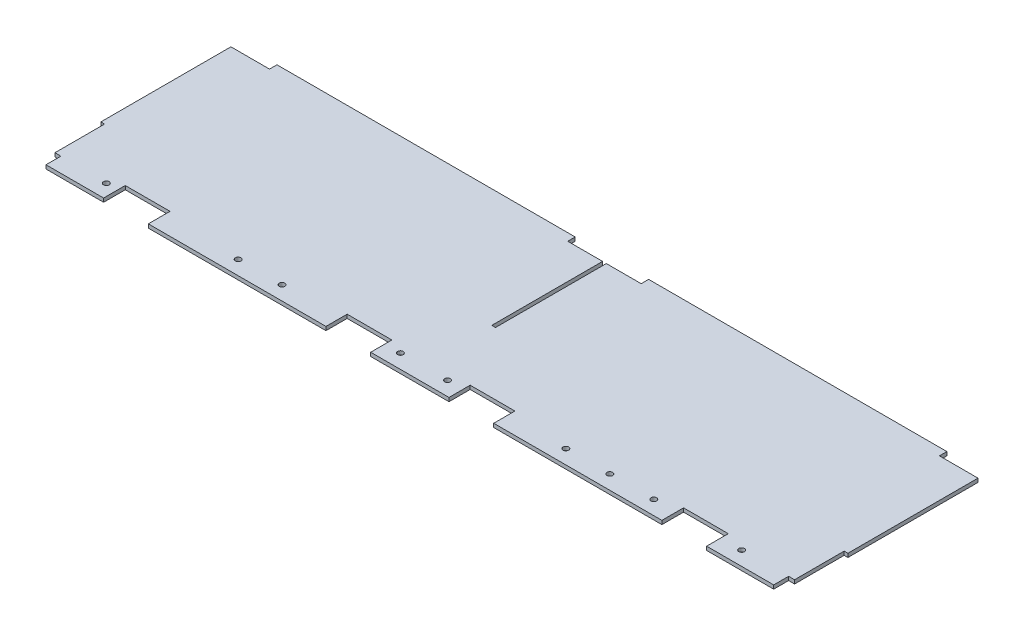
SolidWorks part; units mm, degrees
material "6061-T6 (SS)"
ref_plane "X-Y Datum" through (0, 0, 0) normal (0, 0, 1) x (1, 0, 0)
ref_plane "X-Z Datum" through (0, 0, 0) normal (0, 1, 0) x (1, 0, 0)
ref_plane "Y-Z Datum" through (0, 0, 0) normal (1, 0, 0) x (0, 0, -1)
sketch "Sketch1" plane through (0, 0, 0) normal (0, 1, 0) x (1, 0, 0)
  line L1 (0, 0) -> (629.9098, 0)
  line L2 (0, 0) -> (0, 147.6985)
  line L3 (0, 147.6985) -> (629.9098, 147.6985)
  line L4 (629.9098, 0) -> (629.9098, 147.6985)
extrude "Boss-Extrude1" add sketch "Sketch1" along normal blind 3.175
sketch "Sketch3" plane through (0, 0, -147.6985) normal (0, 0, -1) x (-1, 0, 0)
  line L0 (-629.9098, 0) -> (0, 0) construction
  line L1 (-629.9098, 0) -> (-629.9098, 3.175) construction
  line L2 (-629.9098, 3.175) -> (0, 3.175) construction
  line L3 (0, 0) -> (0, 3.175) construction
  line L4 (-600.2261, 0) -> (-346.2261, 0)
  line L5 (-600.2261, 0) -> (-600.2261, 3.175)
  line L6 (-600.2261, 3.175) -> (-346.2261, 3.175)
  line L7 (-346.2261, 0) -> (-346.2261, 3.175)
  line L8 (-283.6837, 0) -> (-29.6837, 0)
  line L9 (-283.6837, 0) -> (-283.6837, 3.175)
  line L10 (-283.6837, 3.175) -> (-29.6837, 3.175)
  line L11 (-29.6837, 0) -> (-29.6837, 3.175)
extrude "Boss-Extrude2" add sketch "Sketch3" along normal blind 6.35
sketch "Sketch4" plane through (0, 3.175, 0) normal (0, 1, 0) x (1, 0, 0)
  line L0 (346.2261, 147.6985) -> (283.6837, 147.6985) construction
  line L1 (313.3674, 53.332) -> (316.5424, 53.332)
  line L2 (313.3674, 53.332) -> (313.3674, 242.0649)
  line L3 (313.3674, 242.0649) -> (316.5424, 242.0649)
  line L4 (316.5424, 53.332) -> (316.5424, 242.0649)
  line L5 (313.3674, 53.332) -> (316.5424, 242.0649) construction
  line L6 (313.3674, 242.0649) -> (316.5424, 53.332) construction
  point P0 (314.9549, 147.6985)
extrude "Cut-Extrude1" cut sketch "Sketch4" against normal blind 3.175
sketch "Sketch6" plane through (0, 3.175, 0) normal (0, 1, 0) x (1, 0, 0)
  line L0 (314.9549, 53.332) -> (314.9549, 202.815) construction
  line L6 (629.9098, 36.9246) -> (633.0848, 36.9246)
  line L7 (633.0848, 147.6985) -> (633.0848, 36.9246)
  line L8 (629.9098, 147.6985) -> (633.0848, 147.6985)
  line L9 (629.9098, 147.6985) -> (629.9098, 36.9246)
  line L10 (0, 147.6985) -> (0, 36.9246)
  line L11 (0, 147.6985) -> (-3.175, 147.6985)
  line L12 (-3.175, 147.6985) -> (-3.175, 36.9246)
  line L13 (0, 36.9246) -> (-3.175, 36.9246)
extrude "Boss-Extrude4" add sketch "Sketch6" against normal blind 3.175
sketch "Sketch8" plane through (0, 3.175, 0) normal (0, 1, 0) x (1, 0, 0)
  line L1 (0, 0) -> (629.9098, 0)
  line L2 (0, 0) -> (0, -18.0442)
  line L3 (0, -18.0442) -> (629.9098, -18.0442)
  line L4 (629.9098, 0) -> (629.9098, -18.0442)
extrude "Boss-Extrude5" add sketch "Sketch8" against normal through all
sketch "Sketch9" plane through (0, 3.175, 0) normal (0, 1, 0) x (1, 0, 0)
  line L0 (0, -18.0442) -> (47.8104, -18.0442) construction
  line L1 (0, -18.0442) -> (629.9098, -18.0442) construction
  line L2 (314.9549, -18.0442) -> (314.9549, 180.2876) construction
  line L3 (30.0304, -36.0782) -> (65.5904, -36.0782)
  line L4 (30.0304, -36.0782) -> (30.0304, -0.0102)
  line L5 (30.0304, -0.0102) -> (65.5904, -0.0102)
  line L6 (65.5904, -36.0782) -> (65.5904, -0.0102)
  line L7 (30.0304, -36.0782) -> (65.5904, -0.0102) construction
  line L8 (30.0304, -0.0102) -> (65.5904, -36.0782) construction
  line L9 (599.8794, -0.0102) -> (564.3194, -0.0102)
  line L10 (564.3194, -36.0782) -> (564.3194, -0.0102)
  line L11 (599.8794, -36.0782) -> (564.3194, -36.0782)
  line L12 (599.8794, -36.0782) -> (599.8794, -0.0102)
extrude "Cut-Extrude2" [suppressed] cut sketch "Sketch9" against normal through all
sketch "Sketch10" plane through (0, 3.175, 0) normal (0, 1, 0) x (1, 0, 0)
  line L0 (313.3674, 53.332) -> (313.3674, -18.0442) construction
  line L1 (314.9549, -18.0442) -> (314.9549, -25.2417) construction
  line L2 (0, -18.0442) -> (629.9098, -18.0442) construction
  line L3 (313.3674, -18.0442) -> (281.6174, -18.0442) construction
  line L4 (348.2924, 0) -> (386.3924, 0) construction
  line L5 (281.6174, -18.0442) -> (243.5174, -18.0442) construction
  line L6 (281.6174, -18.0442) -> (281.6174, 0) construction
  line L7 (281.6174, 0) -> (243.5174, 0) construction
  line L8 (243.5174, -18.0442) -> (243.5174, 0) construction
  line L9 (386.3924, -18.0442) -> (386.3924, 0) construction
  line L10 (348.2924, -18.0442) -> (386.3924, -18.0442) construction
  line L11 (348.2924, -18.0442) -> (348.2924, 0) construction
  line L12 (0, -18.0442) -> (50.8, -18.0442) construction
  line L13 (0, -18.0442) -> (629.9098, -18.0442) construction
  line L22 (598.1598, 0) -> (560.0598, 0)
  line L23 (31.75, -36.0883) -> (69.85, -36.0883)
  line L24 (31.75, -36.0883) -> (31.75, 0)
  line L25 (31.75, 0) -> (69.85, 0)
  line L26 (69.85, -36.0883) -> (69.85, 0)
  line L27 (31.75, -36.0883) -> (69.85, 0) construction
  line L28 (31.75, 0) -> (69.85, -36.0883) construction
  line L29 (560.0598, -36.0883) -> (560.0598, 0)
  line L30 (598.1598, -36.0883) -> (560.0598, -36.0883)
  line L31 (598.1598, -36.0883) -> (598.1598, 0)
  line L32 (0, 36.9246) -> (0, -18.0442) construction
  dimension "D1" = 31.75
  dimension "D2" = 38.1
  dimension "D3" = 50.8
extrude "Cut-Extrude3" cut sketch "Sketch10" against normal through all
sketch "Sketch11" plane through (0, 3.175, 0) normal (0, 1, 0) x (1, 0, 0)
  line L2 (0, -18.0442) -> (0, -137.4242)
  line L3 (0, -137.4242) -> (629.9098, -137.4242)
  line L4 (629.9098, -18.0442) -> (629.9098, -137.4242)
  line L5 (314.9549, -18.0442) -> (629.9098, -137.4242) construction
  line L6 (0, -137.4242) -> (314.9549, -18.0442) construction
  line L7 (0, -18.0442) -> (31.75, -18.0442)
  line L8 (281.6174, -18.0442) -> (348.2924, -18.0442)
  line L10 (243.5174, -18.0442) -> (243.5174, -26.9519) construction
  line L11 (243.5174, -26.9519) -> (281.6174, -26.9519) construction
  line L12 (281.6174, -18.0442) -> (281.6174, -26.9519) construction
  line L14 (348.2924, -18.0442) -> (348.2924, -27.0662) construction
  line L15 (348.2924, -27.0662) -> (386.3924, -27.0662) construction
  line L16 (386.3924, -18.0442) -> (386.3924, -27.0662) construction
  line L17 (386.3924, -18.0442) -> (560.0598, -18.0442)
  line L18 (31.75, -18.0442) -> (31.75, -26.9519)
  line L19 (31.75, -26.9519) -> (69.85, -26.9519)
  line L20 (69.85, -26.9519) -> (69.85, -18.0442)
  line L21 (560.0598, -18.0442) -> (560.0598, -27.0662)
  line L22 (560.0598, -27.0662) -> (598.1598, -27.0662)
  line L23 (598.1598, -27.0662) -> (598.1598, -18.0442)
  line L24 (69.85, -18.0442) -> (243.5174, -18.0442)
  line L25 (598.1598, -18.0442) -> (629.9098, -18.0442)
  line L26 (243.5174, -18.0442) -> (281.6174, -18.0442)
  line L27 (348.2924, -18.0442) -> (386.3924, -18.0442)
  point P0 (314.9549, -18.0442)
extrude "Boss-Extrude6" [suppressed] add sketch "Sketch11" against normal through all
sketch "Sketch12" plane through (0, 3.175, 0) normal (0, 1, 0) x (1, 0, 0)
  line L1 (31.75, 0) -> (69.85, 0)
  line L2 (31.75, 0) -> (31.75, -18.0442)
  line L3 (31.75, -18.0442) -> (69.85, -18.0442)
  line L4 (69.85, 0) -> (69.85, -18.0442)
  line L5 (560.0598, 0) -> (598.1598, 0)
  line L6 (560.0598, 0) -> (560.0598, -18.0442)
  line L7 (560.0598, -18.0442) -> (598.1598, -18.0442)
  line L8 (598.1598, 0) -> (598.1598, -18.0442)
extrude "Boss-Extrude7" add sketch "Sketch12" against normal through all
sketch "Sketch13" [suppressed] plane through (0, 0, 0) normal (0, -1, 0) x (1, 0, 0)
  line L0 (244.9105, 120.8318) -> (233.5527, 120.8318) construction
  line L1 (244.9105, 100.8318) -> (233.5527, 100.8318) construction
  line L2 (249.2316, 73.2621) -> (249.2316, 61.9043) construction
  line L3 (229.2316, 73.2621) -> (229.2316, 61.9043) construction
  line L4 (245.0431, 100.3238) -> (233.42, 100.3238)
  line L5 (245.0431, 121.3398) -> (233.42, 121.3398)
  line L6 (249.7396, 73.3947) -> (249.7396, 61.7716)
  line L7 (228.7236, 73.3947) -> (228.7236, 61.7716)
  line L8 (2.2083, 136.32) -> (632.1181, 136.32) construction
  line L9 (2.2083, 136.32) -> (2.2083, 49.1456) construction
  line L10 (2.2083, 49.1456) -> (632.1181, 49.1456) construction
  line L11 (632.1181, 136.32) -> (632.1181, 49.1456) construction
  circle A0 centre (227.7316, 122.3318) radius 1.55
  circle A1 centre (250.7316, 122.3318) radius 1.55
  circle A2 centre (227.7316, 99.3318) radius 1.55
  circle A3 centre (250.7316, 99.3318) radius 1.55
  circle A4 centre (152.3285, 95.8779) radius 11.049
  circle A5 centre (227.7316, 79.0832) radius 1.55
  circle A6 centre (227.7316, 56.0832) radius 1.55
  circle A7 centre (250.7316, 56.0832) radius 1.55
  circle A8 centre (250.7316, 79.0832) radius 1.55
  arc A9 (249.2316, 73.2621) -> (229.2316, 73.2621) centre (239.2316, 67.5832) ccw construction
  arc A10 (249.2316, 61.9043) -> (229.2316, 61.9043) centre (239.2316, 67.5832) cw construction
  arc A11 (244.9105, 120.8318) -> (244.9105, 100.8318) centre (239.2316, 110.8318) cw construction
  arc A12 (233.5527, 120.8318) -> (233.5527, 100.8318) centre (239.2316, 110.8318) ccw construction
  arc A13 (233.42, 121.3398) -> (233.42, 100.3238) centre (239.2316, 110.8318) ccw
  arc A14 (245.0431, 121.3398) -> (245.0431, 100.3238) centre (239.2316, 110.8318) cw
  arc A15 (249.7396, 61.7716) -> (228.7236, 61.7716) centre (239.2316, 67.5832) cw
  arc A16 (249.7396, 73.3947) -> (228.7236, 73.3947) centre (239.2316, 67.5832) ccw
extrude "Cut-Extrude4" [suppressed] cut sketch "Sketch13" against normal through all
sketch "Sketch14" [suppressed] plane through (0, 0, 0) normal (0, -1, 0) x (1, 0, 0)
  line L0 (0, 137.4242) -> (653.3937, 137.4242) construction
  line L1 (0, 137.4242) -> (0, -17.9044) construction
  line L2 (0, -17.9044) -> (653.3937, -17.9044) construction
  line L3 (653.3937, 137.4242) -> (653.3937, -17.9044) construction
  point P0 (11.811, 127.2642)
  point P1 (163.383, 127.2642)
  point P2 (314.9549, 127.2642)
  point P3 (466.5269, 127.2642)
  point P4 (618.0988, 127.2642)
  point P5 (618.0988, 38.1102)
  point P6 (466.5269, 38.1102)
  point P7 (314.9549, 38.1102)
  point P8 (163.383, 38.1102)
  point P9 (11.811, 38.1102)
sketch "Sketch17" plane through (0, 3.175, 0) normal (0, 1, 0) x (1, 0, 0)
  line L1 (243.5174, -18.0442) -> (281.6174, -18.0442)
  line L2 (243.5174, -18.0442) -> (243.5174, 0)
  line L3 (243.5174, 0) -> (281.6174, 0)
  line L4 (281.6174, -18.0442) -> (281.6174, 0)
  line L5 (348.2924, -18.0442) -> (386.3924, -18.0442)
  line L6 (348.2924, -18.0442) -> (348.2924, 0)
  line L7 (348.2924, 0) -> (386.3924, 0)
  line L8 (386.3924, -18.0442) -> (386.3924, 0)
extrude "Cut-Extrude5" cut sketch "Sketch17" against normal through all
sketch "Sketch18" plane through (0, 3.175, 0) normal (0, 1, 0) x (1, 0, 0)
  line L0 (0, 36.9246) -> (0, -18.0442) construction
  line L1 (54.1274, 0.4059) -> (92.2274, 0.4059)
  line L2 (54.1274, 0.4059) -> (54.1274, -18.0442)
  line L3 (54.1274, -18.0442) -> (92.2274, -18.0442)
  line L4 (92.2274, 0.4059) -> (92.2274, -18.0442)
  line L10 (314.752, 53.332) -> (314.752, 40.2478) construction
  line L16 (386.3924, -18.0442) -> (629.9098, -18.0442) construction
  line L17 (567.7073, -18.0442) -> (529.6073, -18.0442)
  line L18 (567.7073, -18.0442) -> (567.7073, 0.4059)
  line L19 (567.7073, 0.4059) -> (529.6073, 0.4059)
  line L20 (529.6073, -18.0442) -> (529.6073, 0.4059)
  line L21 (0, -18.0442) -> (243.5174, -18.0442) construction
  line L22 (629.9098, -18.0442) -> (629.9098, 36.9246) construction
  dimension "D1" = 38.1
  dimension "D2" = 54.1274
  dimension "D3" = 38.1
  dimension "D4" = 62.2025
extrude "Cut-Extrude6" cut sketch "Sketch18" against normal through all
sketch "Sketch20" [suppressed] plane through (0, 0, 0) normal (0, -1, 0) x (1, 0, 0)
  line L0 (269.9465, 71.4811) -> (278.9364, 71.4811)
  line L1 (258.3414, 113.1615) -> (278.9364, 113.1615)
  line L2 (258.3414, 113.1615) -> (258.3414, 110.2194)
  line L3 (258.3414, 110.2194) -> (278.9364, 110.2194)
  line L4 (278.9364, 113.1615) -> (278.9364, 110.2194)
  line L5 (258.3414, 71.4811) -> (266.1871, 71.4811)
  line L6 (258.3414, 71.4811) -> (258.3414, 69.3563)
  line L7 (258.3414, 69.3563) -> (266.1871, 69.3563)
  line L8 (278.9364, 71.4811) -> (278.9364, 69.3563)
  line L9 (266.1871, 79) -> (269.9465, 79)
  line L10 (266.1871, 79) -> (266.1871, 71.4811)
  line L11 (266.1871, 61.8375) -> (269.9465, 61.8375)
  line L12 (269.9465, 79) -> (269.9465, 71.4811)
  line L13 (269.9465, 69.3563) -> (269.9465, 61.8375)
  line L14 (269.9465, 69.3563) -> (278.9364, 69.3563)
  line L15 (266.1871, 69.3563) -> (266.1871, 61.8375)
extrude "Cut-Extrude7" [suppressed] cut sketch "Sketch20" against normal blind 1.27
sketch "Sketch21" [suppressed] plane through (0, 3.175, 0) normal (0, 1, 0) x (1, 0, 0)
  line L0 (0, -137.4242) -> (8.6479, -137.4242) construction
  line L1 (0, -137.4242) -> (0, -125.2168) construction
  line L2 (0, -125.2168) -> (8.6479, -125.2168) construction
  line L3 (8.6479, -137.4242) -> (8.6479, -125.2168) construction
  line L4 (314.9549, 53.332) -> (314.9549, 36.3364) construction
  line L5 (313.3674, 53.332) -> (316.5424, 53.332) construction
  circle A1 centre (168.9435, -126.7866) radius 2.25
  circle A2 centre (314.9549, -126.7866) radius 2.25
  circle A3 centre (460.9663, -126.7866) radius 2.25
  circle A4 centre (606.9777, -126.7866) radius 2.25
  circle A5 centre (22.9321, -126.7866) radius 2.25
  point P1 (168.9435, -126.7866)
  point P2 (314.9549, -126.7866)
  point P3 (460.9663, -126.7866)
  point P4 (606.9777, -126.7866)
  point P9 (0, -137.4242)
extrude "Cut-Extrude8" [suppressed] cut sketch "Sketch21" against normal through all
sketch "Sketch22" plane through (0, 3.175, 0) normal (0, 1, 0) x (1, 0, 0)
  circle A0 centre (313.8515, -5.238) radius 5.238
extrude "Cut-Extrude9" [suppressed] cut sketch "Sketch22" against normal through all
sketch "Sketch23" [suppressed] plane through (0, 3.175, 0) normal (0, 1, 0) x (1, 0, 0)
  line L0 (538.3475, -12.829) -> (538.3475, -6.729) construction
  line L1 (375.4057, -12.829) -> (375.4057, -6.729) construction
  line L2 (254.5042, -12.829) -> (254.5042, -6.729) construction
  line L3 (91.5623, -12.829) -> (91.5623, -6.729) construction
  line L4 (629.9098, -137.4242) -> (403.1779, -137.4242) construction
  line L5 (629.9098, -137.4242) -> (629.9098, -43.8281) construction
  line L6 (629.9098, -43.8281) -> (403.1779, -43.8281) construction
  line L7 (403.1779, -137.4242) -> (403.1779, -43.8281) construction
  circle A0 centre (538.3475, -9.779) radius 2.25
  circle A1 centre (375.4057, -9.779) radius 2.25
  circle A2 centre (254.5042, -9.779) radius 2.25
  circle A3 centre (91.5623, -9.779) radius 2.25
  point P20 (629.9098, -137.4242)
extrude "Cut-Extrude10" [suppressed] cut sketch "Sketch23" against normal through all
sketch "Sketch24" plane through (0, 3.175, 0) normal (0, 1, 0) x (1, 0, 0)
  line L0 (314.9549, -18.0442) -> (314.9549, -44.4855) construction
  line L1 (0, -18.0442) -> (5.08, -18.0442)
  line L2 (0, -18.0442) -> (0, -5.3442)
  line L3 (0, -5.3442) -> (5.08, -5.3442)
  line L4 (5.08, -18.0442) -> (5.08, -5.3442)
  line L6 (629.9098, -5.3442) -> (624.8298, -5.3442)
  line L7 (624.8298, -18.0442) -> (624.8298, -5.3442)
  line L8 (629.9098, -18.0442) -> (624.8298, -18.0442)
  line L9 (629.9098, -18.0442) -> (629.9098, -5.3442)
extrude "Cut-Extrude11" cut sketch "Sketch24" against normal through all
sketch "Sketch27" [suppressed] plane through (0, 3.175, 0) normal (0, 1, 0) x (1, 0, 0)
  circle A0 centre (134.368, -77.9173) radius 2.4
  circle A1 centre (170.289, -77.9173) radius 2.4
  circle A2 centre (170.289, -113.8384) radius 2.4
  circle A3 centre (134.368, -113.8384) radius 2.4
  point P4 (152.3285, -95.8779)
extrude "Cut-Extrude12" [suppressed] cut sketch "Sketch27" against normal through all
sketch "Sketch28" [suppressed] plane through (0, 3.175, 0) normal (0, 1, 0) x (1, 0, 0)
  line L0 (629.9098, -18.0442) -> (0, -18.0442) construction
  line L1 (629.9098, -18.0442) -> (629.9098, 147.6985) construction
  line L2 (629.9098, 147.6985) -> (0, 147.6985) construction
  line L3 (0, -18.0442) -> (0, 147.6985) construction
  line L4 (613.8026, -5.9968) -> (609.002, -5.9968)
  line L5 (513.0512, -5.9968) -> (508.2506, -5.9968)
  line L6 (475.6264, -5.9968) -> (470.8258, -5.9968)
  line L7 (438.2017, -5.9968) -> (433.4011, -5.9968)
  line L8 (337.45, -5.9968) -> (332.6497, -5.9968)
  line L9 (314.9549, 53.332) -> (314.9549, 20.4386) construction
  line L10 (292.4599, -5.9968) -> (297.2602, -5.9968)
  line L11 (191.7082, -5.9968) -> (196.5088, -5.9968)
  line L12 (154.2834, -5.9968) -> (159.084, -5.9968)
  line L13 (116.8586, -5.9968) -> (121.6592, -5.9968)
  line L14 (16.1072, -5.9968) -> (20.9078, -5.9968)
hole_wizard "M4 Clearance Hole2" [suppressed] positions "Sketch29" profile "Sketch30" hole size "M4" standard "ANSI Metric"
sketch "Sketch29" plane through (0, 3.175, 0) normal (0, 1, 0) x (1, 0, 0)
  line L0 (16.1072, -5.9968) -> (20.9078, -5.9968) construction
  line L1 (116.8586, -5.9968) -> (121.6592, -5.9968) construction
  line L2 (154.2834, -5.9968) -> (159.084, -5.9968) construction
  line L3 (191.7082, -5.9968) -> (196.5088, -5.9968) construction
  line L4 (292.4599, -5.9968) -> (297.2602, -5.9968) construction
  line L5 (337.45, -5.9968) -> (332.6497, -5.9968) construction
  line L6 (438.2017, -5.9968) -> (433.4011, -5.9968) construction
  line L7 (475.6264, -5.9968) -> (470.8258, -5.9968) construction
  line L8 (513.0512, -5.9968) -> (508.2506, -5.9968) construction
  line L9 (613.8026, -5.9968) -> (609.002, -5.9968) construction
  point P0 (18.5075, -5.9968)
  point P4 (119.2589, -5.9968)
  point P8 (156.6837, -5.9968)
  point P12 (194.1085, -5.9968)
  point P16 (294.86, -5.9968)
  point P20 (335.0498, -5.9968)
  point P24 (435.8014, -5.9968)
  point P28 (473.2261, -5.9968)
  point P32 (510.6509, -5.9968)
  point P36 (611.4023, -5.9968)
sketch "Sketch30" plane through (18.5075, 3.175, 5.9968) normal (1, 0, 0) x (0, 0, 1)
  line L0 (0, 0) -> (0, 3.175)
  line L1 (0, 3.175) -> (2.4, 3.175)
  line L2 (2.4, 3.175) -> (2.4, 0)
  line L5 (2.4, 0) -> (0, 0)
  line L11 (0, -6.35) -> (0, 107.95) construction
  dimension "Thru Hole Dia." = 4.8
  dimension "Thru Hole Depth" = 3.175
sketch "Sketch31" plane through (0, 3.175, 0) normal (0, 1, 0) x (1, 0, 0)
  line L5 (624.8298, -18.0442) -> (624.8298, -5.3442) construction
  line L6 (5.08, -5.3442) -> (624.8298, -5.3442) construction
  line L7 (5.08, -18.0442) -> (5.08, -5.3442) construction
  line L8 (5.08, -18.0442) -> (624.8298, -18.0442) construction
  point P24 (5.08, -18.0442)
  point P25 (585.5004, -5.9968)
  point P26 (510.6509, -5.9968)
  point P27 (473.2261, -5.9968)
  point P28 (435.8014, -5.9968)
  point P29 (335.05, -5.9968)
  point P30 (294.8599, -5.9968)
  point P31 (194.1085, -5.9968)
  point P32 (156.6837, -5.9968)
  point P33 (44.4094, -5.9968)
hole_wizard "M4 Clearance Hole3" positions "Sketch34" profile "Sketch35" hole size "M4" standard "ANSI Metric" end condition through all
sketch "Sketch34" plane through (0, 3.175, 0) normal (0, 1, 0) x (1, 0, 0)
  point P0 (44.4094, -5.9968)
  point P3 (156.6837, -5.9968)
  point P6 (194.1085, -5.9968)
  point P9 (294.8599, -5.9968)
  point P12 (335.05, -5.9968)
  point P15 (435.8014, -5.9968)
  point P18 (473.2261, -5.9968)
  point P21 (510.6509, -5.9968)
  point P24 (585.5004, -5.9968)
sketch "Sketch35" plane through (44.4094, 3.175, 5.9968) normal (1, 0, 0) x (0, 0, 1)
  line L0 (0, 0) -> (0, 3.175)
  line L1 (0, 3.175) -> (2.4, 3.175)
  line L2 (2.4, 3.175) -> (2.4, 0)
  line L5 (2.4, 0) -> (0, 0)
  line L11 (0, -6.35) -> (0, 107.95) construction
  dimension "Thru Hole Dia." = 4.8
  dimension "Thru Hole Depth" = 3.175
